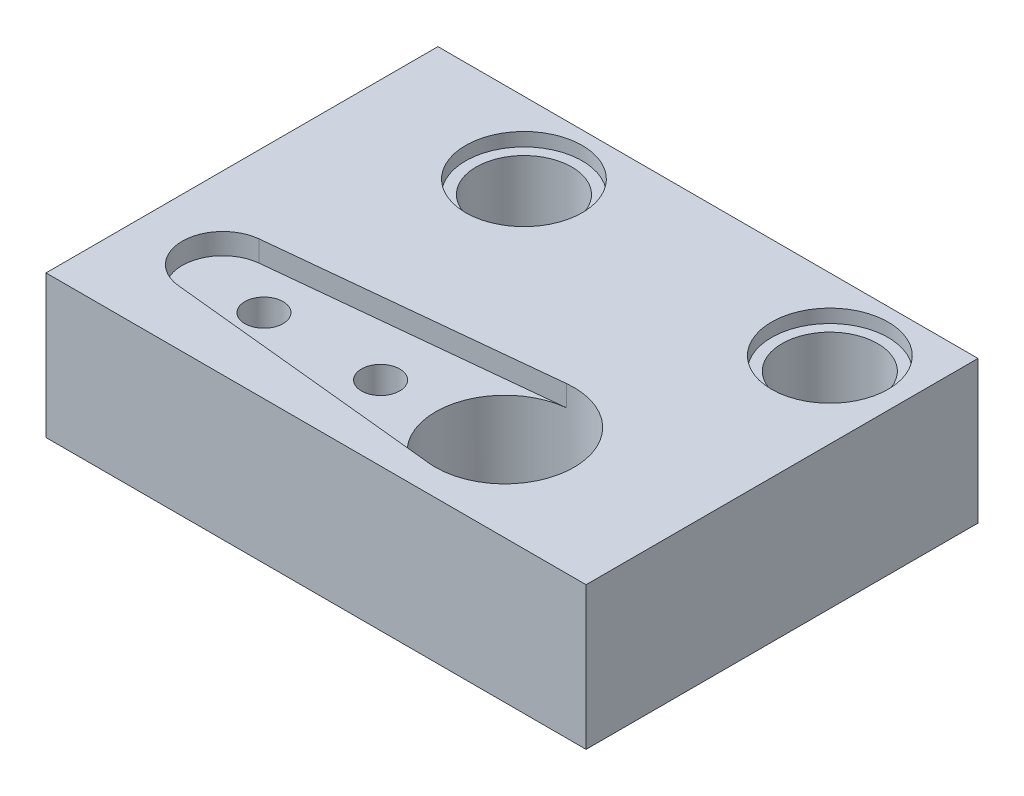
SolidWorks part; units mm, degrees
ref_plane "Front Plane" through (0, 0, 0) normal (0, 0, 1) x (1, 0, 0)
ref_plane "Top Plane" through (0, 0, 0) normal (0, 1, 0) x (1, 0, 0)
ref_plane "Right Plane" through (0, 0, 0) normal (1, 0, 0) x (0, 0, -1)
sketch "Sketch1" plane through (0, 0, 0) normal (0, 1, 0) x (1, 0, 0)
  line L0 (0, 12.1071) -> (0, -10.3651) construction
  line L1 (-19.1976, 0) -> (16.8443, 0) construction
  line L2 (-14.75, 6.703) -> (-14.75, -5.4465) construction
  line L3 (9.25, 15.5) -> (-19, 15.5)
  line L4 (-19, 15.5) -> (-19, -5)
  line L5 (9.25, 15.5) -> (9.25, -5)
  line L6 (-19, 11.75) -> (9.25, 11.75) construction
  line L7 (-4.875, 15.5) -> (-4.875, -5.7439) construction
  line L8 (0, 3.6062) -> (9.25, 3.6062) construction
  line L9 (-14.9661, 2.114) -> (-0.3686, 3.6062) construction
  line L10 (9.25, -4.25) -> (-19, -4.25) construction
  line L11 (-19, -5) -> (9.25, -5)
  circle A0 centre (0, 0) radius 3.625 construction
  circle A1 centre (-14.75, 0) radius 2.125 construction
  circle A2 centre (5.25, 11.75) radius 2.5
  circle A3 centre (-10.75, 11.75) radius 2.5
  point P28 (9.25, 0)
  point P29 (-19, 0)
  dimension "D2" = 7.25
  dimension "D3" = 4.25
  dimension "D7" = 3.75
  dimension "D8" = 5
  dimension "D10" = 5
  dimension "D1" = 14.75
  dimension "D4" = 9.25
  dimension "D5" = 4.25
  dimension "D6" = 15.5
  dimension "D9" = 4
  dimension "D11" = 16
  dimension "D12" = 16
  dimension "D13" = 5
extrude "Boss-Extrude1" add sketch "Sketch1" along normal blind 7.46
sketch "Sketch3" plane through (0, 7.46, 0) normal (0, 1, 0) x (1, 0, 0)
  line L0 (9.25, 0) -> (-19, 0) construction
  line L1 (9.25, -5) -> (9.25, 15.5) construction
  line L2 (-19, 15.5) -> (-19, -5) construction
  line L3 (-19, -5) -> (9.25, -5) construction
  line L4 (-4.875, 15.5) -> (-4.875, -5) construction
  line L5 (9.25, 15.5) -> (-19, 15.5) construction
  line L6 (0, 15.5) -> (0, -5) construction
  line L7 (-14.75, 15.5) -> (-14.75, -5) construction
  line L8 (-14.9655, 2.114) -> (-0.3671, 3.6019)
  line L9 (-14.9655, -2.114) -> (-0.3671, -3.6019)
  arc A0 (-0.3671, -3.6019) -> (-0.3671, 3.6019) centre (0, 0) ccw
  arc A1 (-14.9655, 2.114) -> (-14.9655, -2.114) centre (-14.75, 0) ccw
  dimension "D4" = 4.25
  dimension "D5" = 7.2411
  dimension "D1" = 5
  dimension "D2" = 9.25
  dimension "D3" = 14.75
extrude "Cut-Extrude2" cut sketch "Sketch3" against normal blind 1.1
sketch "Sketch5" plane through (0, 6.36, 0) normal (0, 1, 0) x (1, 0, 0)
  line L0 (0, 3.6205) -> (0, -3.6205) construction
  line L1 (3.6205, 0) -> (-16.875, 0) construction
  line L2 (-6.5, 2.7009) -> (-6.5, -2.6251) construction
  line L3 (-12.6, 1.7656) -> (-12.6, -1.377) construction
  arc A0 (-0.3671, -3.6019) -> (-0.3671, 3.6019) centre (0, 0) ccw construction
  arc A1 (-14.9655, 2.114) -> (-14.9655, -2.114) centre (-14.75, 0) ccw construction
  circle A2 centre (-12.6, 0) radius 1
  circle A3 centre (-6.5, 0) radius 1
  circle A4 centre (0, 0) radius 3.6205
  dimension "D3" = 2
  dimension "D4" = 2
  dimension "D1" = 6.5
  dimension "D2" = 12.6
extrude "Cut-Extrude3" cut sketch "Sketch5" against normal through all
sketch "Sketch6" plane through (0, 7.46, 0) normal (0, 1, 0) x (1, 0, 0)
  circle A0 centre (-10.75, 11.75) radius 3.05
  circle A1 centre (5.25, 11.75) radius 3.05
  dimension "D1" = 6.1
  dimension "D2" = 6.1
extrude "Cut-Extrude4" cut sketch "Sketch6" against normal blind 0.7
sketch "Sketch7" plane through (0, 0, 0) normal (0, -1, 0) x (1, 0, 0)
  circle A0 centre (5.25, -11.75) radius 3.05
  circle A1 centre (-10.75, -11.75) radius 3.05
  dimension "D1" = 6.1
  dimension "D2" = 6.1
extrude "Cut-Extrude5" cut sketch "Sketch7" against normal blind 0.7
sketch "Sketch4" plane through (0, 7.46, 0) normal (0, 1, 0) x (1, 0, 0)
  line L0 (0, 15.5) -> (0, -5) construction
  line L1 (9.25, 15.5) -> (-19, 15.5) construction
  line L2 (-19, -5) -> (9.25, -5) construction
  line L3 (9.25, -5) -> (9.25, 15.5) construction
  line L4 (-14.25, 15.5) -> (-14.25, -5) construction
  dimension "D1" = 9.25
  dimension "D2" = 14.25
